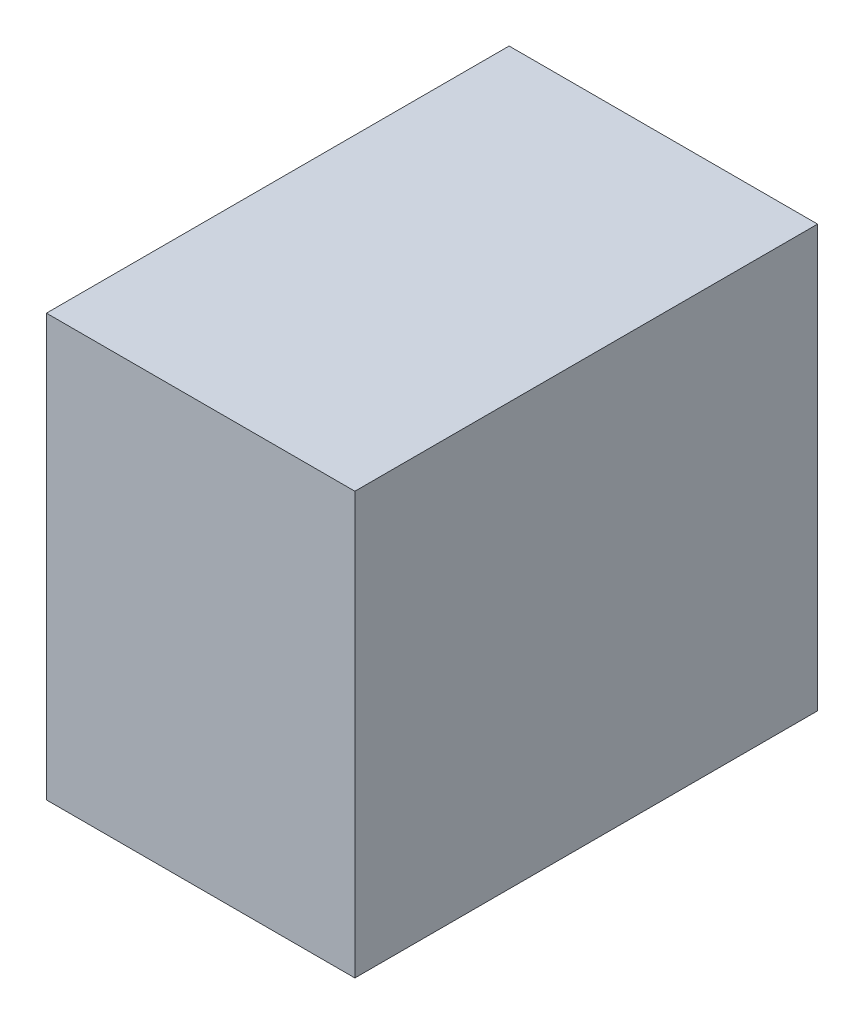
SolidWorks part; units mm, degrees
ref_plane "Front Plane" through (0, 0, 0) normal (0, 0, 1) x (1, 0, 0)
ref_plane "Top Plane" through (0, 0, 0) normal (0, 1, 0) x (1, 0, 0)
ref_plane "Right Plane" through (0, 0, 0) normal (1, 0, 0) x (0, 0, -1)
sketch "Sketch1" plane through (0, 0, 0) normal (0, 0, 1) x (1, 0, 0)
  line L1 (30, -41) -> (-30, -41)
  line L2 (30, -41) -> (30, 41)
  line L3 (30, 41) -> (-30, 41)
  line L4 (-30, -41) -> (-30, 41)
  line L5 (30, -41) -> (-30, 41) construction
  line L6 (30, 41) -> (-30, -41) construction
  point P0 (0, 0)
  dimension "D1" = 60
  dimension "D2" = 82
extrude "Boss-Extrude1" add sketch "Sketch1" along normal blind 90
